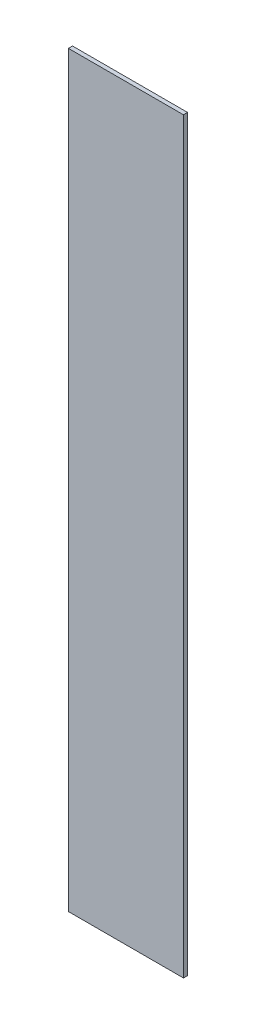
SolidWorks part; units mm, degrees
ref_plane "Front Plane" through (0, 0, 0) normal (0, 0, 1) x (1, 0, 0)
ref_plane "Top Plane" through (0, 0, 0) normal (0, 1, 0) x (1, 0, 0)
ref_plane "Right Plane" through (0, 0, 0) normal (1, 0, 0) x (0, 0, -1)
other "Configuration Table"
sketch "Sketch1" plane through (0, 0, 0) normal (0, 0, 1) x (1, 0, 0)
  line L1 (293, 1469) -> (321, 1469)
  line L2 (293, 1469) -> (293, 1651)
  line L3 (293, 1651) -> (321, 1651)
  line L4 (321, 1469) -> (321, 1651)
extrude "PRESS_kova_kapagi_kulp_cukuru_1" add sketch "Sketch1" along normal blind 1 from offset 26 separate body
